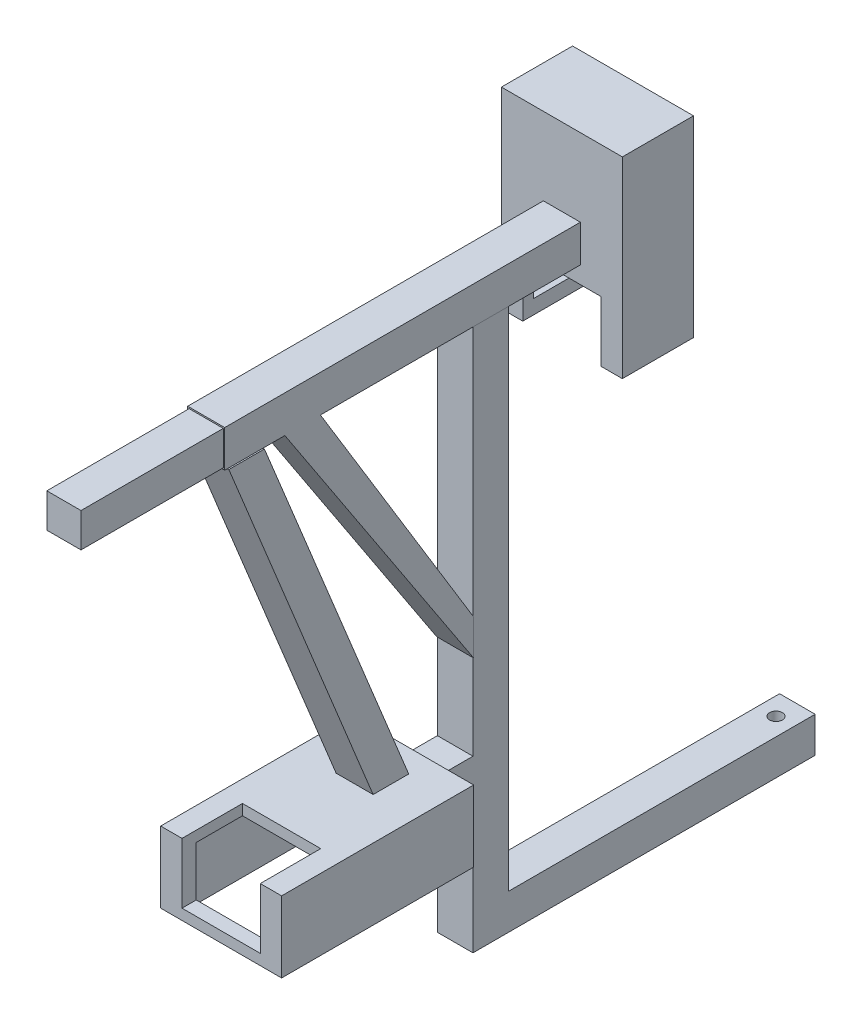
SolidWorks part; units mm, degrees
ref_plane "Front Plane" through (0, 0, 0) normal (0, 0, 1) x (1, 0, 0)
ref_plane "Top Plane" through (0, 0, 0) normal (0, 1, 0) x (1, 0, 0)
ref_plane "Right Plane" through (0, 0, 0) normal (1, 0, 0) x (0, 0, -1)
sketch "Sketch1" plane through (0, 0, 0) normal (0, 0, 1) x (1, 0, 0)
  line L1 (0, 0) -> (4.8, 0)
  line L2 (0, 0) -> (0, -4.8)
  line L3 (0, -4.8) -> (4.8, -4.8)
  line L4 (4.8, 0) -> (4.8, -4.8)
  dimension "D1" = 4.8
  dimension "D2" = 4.8
extrude "Boss-Extrude1" add sketch "Sketch1" along normal blind 20
sketch "Sketch2" plane through (0, 0, 0) normal (0, 0, -1) x (-1, 0, 0)
  line L0 (0, 0) -> (0, -4.8) construction
  line L1 (-5, 0.2) -> (0.2, 0.2)
  line L2 (-5, 0.2) -> (-5, -5)
  line L3 (-5, -5) -> (0.2, -5)
  line L4 (0.2, 0.2) -> (0.2, -5)
  line L5 (-5, 0.2) -> (0.2, -5) construction
  line L6 (-5, -5) -> (0.2, 0.2) construction
  line L7 (-4.8, 0) -> (0, 0) construction
  point P0 (-2.4, -2.4)
  dimension "D1" = 5.2
  dimension "D2" = 5.2
  dimension "D3" = 2.4
  dimension "D4" = 2.4
extrude "Boss-Extrude2" add sketch "Sketch2" along normal blind 50
sketch "Sketch3" plane through (0, 0, -50) normal (0, 0, -1) x (-1, 0, 0)
  line L0 (-5, -5) -> (0.2, -5) construction
  line L1 (-10.9, 11.1) -> (6.1, 11.1)
  line L2 (-10.9, 11.1) -> (-10.9, -15.9)
  line L3 (-10.9, -15.9) -> (6.1, -15.9)
  line L4 (6.1, 11.1) -> (6.1, -15.9)
  line L5 (-10.9, 11.1) -> (6.1, -15.9) construction
  line L6 (-10.9, -15.9) -> (6.1, 11.1) construction
  line L7 (0.2, -5) -> (0.2, 0.2) construction
  point P0 (-2.4, -2.4)
  dimension "D1" = 27
  dimension "D2" = 17
  dimension "D3" = 2.6
  dimension "D4" = 2.6
extrude "Boss-Extrude3" add sketch "Sketch3" along normal blind 10
sketch "Sketch4" plane through (0, 0, -60) normal (0, 0, -1) x (-1, 0, 0)
  line L0 (6.1, 11.1) -> (-10.9, 11.1) construction
  line L1 (4.1, 9.1) -> (-8.9, 9.1)
  line L2 (4.1, 9.1) -> (4.1, -13.9)
  line L3 (4.1, -13.9) -> (-8.9, -13.9)
  line L4 (-8.9, 9.1) -> (-8.9, -13.9)
  line L5 (4.1, 9.1) -> (-8.9, -13.9) construction
  line L6 (4.1, -13.9) -> (-8.9, 9.1) construction
  line L7 (6.1, -15.9) -> (6.1, 11.1) construction
  point P0 (-2.4, -2.4)
  dimension "D1" = 13
  dimension "D2" = 23
  dimension "D3" = 13.5
  dimension "D4" = 8.5
extrude "Cut-Extrude1" cut sketch "Sketch4" against normal blind 8.5
sketch "Sketch5" plane through (0, -15.9, 0) normal (0, -1, 0) x (1, 0, 0)
  line L0 (10.9, -50) -> (-6.1, -50) construction
  line L1 (-3.1, -50) -> (7.9, -50)
  line L2 (-3.1, -50) -> (-3.1, -58.5)
  line L3 (-3.1, -58.5) -> (7.9, -58.5)
  line L4 (7.9, -50) -> (7.9, -58.5)
  line L5 (10.9, -60) -> (-6.1, -60) construction
  line L6 (10.9, -60) -> (10.9, -50) construction
  line L7 (-6.1, -60) -> (-6.1, -50) construction
  point P10 (10.9, -55)
  dimension "D1" = 1.5
  dimension "D2" = 3
  dimension "D3" = 3
extrude "Cut-Extrude2" cut sketch "Sketch5" against normal blind 8.5
sketch "Sketch6" plane through (0, 0.2, 0) normal (0, 1, 0) x (1, 0, 0)
  line L0 (5, 50) -> (5, 0) construction
  line L1 (-0.1, 40) -> (4.9, 40)
  line L2 (-0.1, 40) -> (-0.1, 35)
  line L3 (-0.1, 35) -> (4.9, 35)
  line L4 (4.9, 40) -> (4.9, 35)
  line L5 (-0.1, 40) -> (4.9, 35) construction
  line L6 (-0.1, 35) -> (4.9, 40) construction
  line L7 (-0.2, 50) -> (5, 50) construction
  point P0 (2.4, 37.5)
  dimension "D1" = 5
  dimension "D2" = 5
  dimension "D3" = 2.6
  dimension "D4" = 10
extrude "Boss-Extrude4" add sketch "Sketch6" against normal blind 81.5
sketch "Sketch7" plane through (0, 0, -40) normal (0, 0, -1) x (-1, 0, 0)
  line L0 (0.1, -81.3) -> (0.1, -5) construction
  line L1 (-4.9, -81.3) -> (0.1, -81.3)
  line L2 (-4.9, -81.3) -> (-4.9, -76.3)
  line L3 (-4.9, -76.3) -> (0.1, -76.3)
  line L4 (0.1, -81.3) -> (0.1, -76.3)
  dimension "D1" = 5
  dimension "D2" = 5
extrude "Boss-Extrude5" add sketch "Sketch7" along normal blind 43.1
sketch "Sketch9" plane through (0, -81.3, 0) normal (0, -1, 0) x (1, 0, 0)
  line L0 (-0.1, -35) -> (4.9, -35) construction
  line L1 (4.9, -35) -> (4.9, -83.1) construction
  line L2 (-0.1, -83.1) -> (-0.1, -35) construction
  circle A0 centre (2.4, -80.1) radius 0.9
  dimension "D1" = 45.1
  dimension "D2" = 1.8
  dimension "D3" = 2.5
  dimension "D4" = 2.5
extrude "Cut-Extrude4" cut sketch "Sketch9" against normal through all
sketch "Sketch10" plane through (0, 0, -35) normal (0, 0, 1) x (1, 0, 0)
  line L0 (-0.1, -81.3) -> (-0.1, -5) construction
  line L1 (-0.1, -45.3599) -> (4.9, -45.3599)
  line L2 (-0.1, -45.3599) -> (-0.1, -40.3599)
  line L3 (-0.1, -40.3599) -> (4.9, -40.3599)
  line L4 (4.9, -45.3599) -> (4.9, -40.3599)
  line L5 (4.9, -81.3) -> (4.9, -5) construction
  dimension "D1" = 5
  dimension "D2" = 5
sketch "Sketch11" plane through (0, -5, 0) normal (0, -1, 0) x (1, 0, 0)
  line L0 (-0.2, -50) -> (-0.2, 0) construction
  line L1 (-0.2, -13.4558) -> (5, -13.4558)
  line L2 (-0.2, -13.4558) -> (-0.2, -8.4558)
  line L3 (-0.2, -8.4558) -> (5, -8.4558)
  line L4 (5, -13.4558) -> (5, -8.4558)
  line L5 (5, -50) -> (5, 0) construction
  dimension "D1" = 5
  dimension "D2" = 5.2
sketch "Sketch12" plane through (5, 0, 0) normal (1, 0, 0) x (0, 0, -1)
  line L0 (13.4558, -5) -> (35, -40.3599)
  line L1 (13.4558, -5) -> (8.4558, -5) construction
  line L2 (50, -5) -> (0, -5) construction
  line L3 (35, -45.3599) -> (35, -40.3599) construction
  line L4 (35, -45.3599) -> (35, -40.3599) construction
  line L5 (8.4558, -5) -> (35, -45.3599)
  line L6 (8.4558, -5) -> (13.4558, -5)
  line L7 (35, -40.3599) -> (35, -45.3599)
extrude "Boss-Extrude6" add sketch "Sketch12" against normal blind 5.2
ref_plane "Plane1" through (0, -54.71, 0) normal (0, -1, 0) x (-1, 0, 0)
sketch "Sketch13" plane through (0, -54.71, 0) normal (0, -1, 0) x (-1, 0, 0)
  line L1 (-11.1, 28.9) -> (5.9, 28.9)
  line L2 (-11.1, 28.9) -> (-11.1, 1.9)
  line L3 (-11.1, 1.9) -> (5.9, 1.9)
  line L4 (5.9, 28.9) -> (5.9, 1.9)
  circle A0 centre (-2.4, 80.1) radius 0.9 construction
  dimension "D1" = 51.2
  dimension "D2" = 8.7
  dimension "D3" = 17
  dimension "D4" = 27
extrude "Boss-Extrude7" add sketch "Sketch13" along normal blind 1.5 separate body
sketch "Sketch14" plane through (0, -56.21, 0) normal (0, -1, 0) x (1, 0, 0)
  line L1 (-5.9, -1.9) -> (11.1, -1.9)
  line L2 (-5.9, -1.9) -> (-5.9, -28.9)
  line L3 (-5.9, -28.9) -> (11.1, -28.9)
  line L4 (11.1, -1.9) -> (11.1, -28.9)
  line L5 (-3.9, -3.9) -> (9.1, -3.9)
  line L6 (-3.9, -3.9) -> (-3.9, -26.9)
  line L7 (-3.9, -26.9) -> (9.1, -26.9)
  line L8 (9.1, -3.9) -> (9.1, -26.9)
  point P10 (2.6, -1.9)
  dimension "D1" = 13
  dimension "D2" = 23
  dimension "D3" = 2
  dimension "D4" = 2
extrude "Boss-Extrude8" add sketch "Sketch14" along normal blind 8.5
sketch "Sketch15" plane through (0, 0, -1.9) normal (0, 0, 1) x (1, 0, 0)
  line L0 (11.1, -54.71) -> (-5.9, -54.71) construction
  line L1 (-2.9, -54.71) -> (8.1, -54.71)
  line L2 (-2.9, -54.71) -> (-2.9, -63.21)
  line L3 (-2.9, -63.21) -> (8.1, -63.21)
  line L4 (8.1, -54.71) -> (8.1, -63.21)
  line L5 (11.1, -64.71) -> (11.1, -54.71) construction
  dimension "D1" = 11
  dimension "D2" = 8.5
  dimension "D3" = 3
extrude "Cut-Extrude6" cut sketch "Sketch15" against normal blind 8.5
sketch "Sketch16" plane through (0, 0, -35) normal (0, 0, 1) x (1, 0, 0)
  line L0 (-0.1, -81.3) -> (-0.1, -45.3599) construction
  line L1 (-0.1, -57.3599) -> (4.9, -57.3599)
  line L2 (-0.1, -57.3599) -> (-0.1, -62.3599)
  line L3 (-0.1, -62.3599) -> (4.9, -62.3599)
  line L4 (4.9, -57.3599) -> (4.9, -62.3599)
  line L5 (4.9, -81.3) -> (4.9, -45.3599) construction
  line L6 (-0.1, -45.3599) -> (4.9, -45.3599) construction
  dimension "D1" = 0
  dimension "D2" = 0
  dimension "D3" = 12
  dimension "D4" = 5
extrude "Boss-Extrude9" add sketch "Sketch16" along normal up to next
sketch "Sketch18" plane through (0, 0, 0) normal (1, 0, 0) x (0, 0, -1)
  line L0 (25.666, -54.71) -> (5.3823, -5)
  line L1 (8.4558, -5) -> (0, -5) construction
  line L2 (28.9, -54.71) -> (1.9, -54.71) construction
  line L3 (25.666, -54.71) -> (20.666, -54.71)
  line L4 (20.666, -54.71) -> (0.3823, -5)
  line L5 (0.3823, -5) -> (5.3823, -5)
  dimension "D1" = 49.71
  dimension "D2" = 49.71
  dimension "D3" = 5
  dimension "D4" = 5
extrude "Boss-Extrude10" add sketch "Sketch18" along normal blind 5.2
